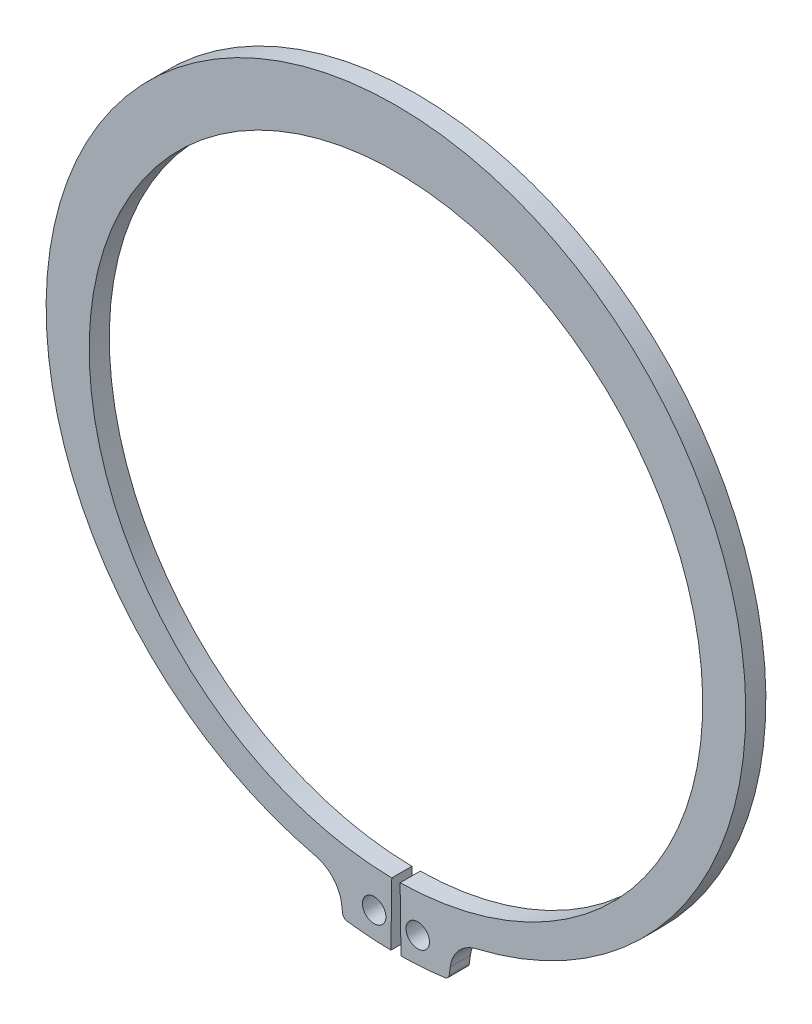
SolidWorks part; units mm, degrees
ref_plane "Plane1" through (0, 0, 0) normal (0, 0, 1) x (1, 0, 0)
ref_plane "Plane2" through (0, 0, 0) normal (0, 1, 0) x (1, 0, 0)
ref_plane "Plane3" through (0, 0, 0) normal (1, 0, 0) x (0, 0, -1)
sketch "Clipboard" plane through (0, 0, 0) normal (0, 0, 1) x (1, 0, 0)
  line L0 (0, 0) -> (8.6, 0)
  line L1 (0, 0) -> (0, 4.3)
  line L2 (0, 0) -> (0, -9.4)
  circle A0 centre (0, 0) radius 1.75
  circle A1 centre (0, 0) radius 47.5
  dimension "HoleDia" = 3.5
  dimension "ShaftDia" = 95
  dimension "LargeSection" = 8.6
  dimension "SmallSection" = 4.3
  dimension "LugSection" = 9.4
sketch "BodySke" plane through (0, 0, 0) normal (0, 0, 1) x (1, 0, 0)
  line L0 (-1.5431, 0) -> (1.5431, 0) construction
  line L1 (0, 0) -> (0, 54.35) construction
  line L2 (0.6222, -45.7458) -> (0.75, -55.1449)
  line L3 (-0.6222, -45.7458) -> (-0.75, -55.1449)
  line L4 (0, 0) -> (13.1537, -53.5584) construction
  line L5 (0, 0) -> (-13.1537, -53.5584) construction
  line L7 (8.0976, -52.8928) -> (7.9493, -54.0185)
  line L8 (-8.0976, -52.8928) -> (-7.9493, -54.0185)
  circle A0 centre (0, 0) radius 45.75 construction
  arc A1 (0.6222, -45.7458) -> (-0.6222, -45.7458) centre (0, 0) ccw
  arc A2 (11.9373, -48.6056) -> (-11.9373, -48.6056) centre (0, 2.1802) ccw construction
  arc A3 (0.75, -55.1449) -> (7.3051, -54.664) centre (0, 0) ccw
  arc A4 (11.9824, -48.595) -> (8.0976, -52.8928) centre (13.1537, -53.5584) ccw
  arc A5 (-8.0976, -52.8928) -> (-11.9824, -48.595) centre (-13.1537, -53.5584) ccw
  arc A6 (-7.3051, -54.664) -> (-0.75, -55.1449) centre (0, 0) ccw
  arc A7 (11.9824, -48.595) -> (-11.9824, -48.595) centre (0, 2.1802) ccw
  arc A8 (-8.395, -50.6338) -> (8.395, -50.6338) centre (0, 0) ccw construction
  circle A9 centre (3.25, -51.222) radius 1.75
  circle A10 centre (-3.25, -51.222) radius 1.75
  arc A11 (7.9493, -54.0185) -> (7.3051, -54.664) centre (7.2058, -53.9207) cw
  arc A12 (-7.9493, -54.0185) -> (-7.3051, -54.664) centre (-7.2058, -53.9207) ccw
  point P28 (7.8748, -54.5849)
  point P31 (-7.8748, -54.5849)
  dimension "HoleDia" = 3.5
  dimension "GrooveDia" = 91.5
  dimension "LugRad" = 55.15
  dimension "HoleOffsetRad" = 51.325
  dimension "D3" = 0.75
  dimension "LargeRad" = 54.35
  dimension "SmallRad" = 50.05
  dimension "SmallAngle" = 27.597
  dimension "D2" = 15
  dimension "HoleSpacing" = 6.5
  dimension "Gap" = 1.5
extrude "Body" add sketch "BodySke" against normal blind 3
sketch "NotSke" plane through (0, 0, 0) normal (0, 0, 1) x (1, 0, 0)
  line L0 (3.25, -49.472) -> (3.25, -52.972)
  line L1 (3.25, -52.972) -> (-3.25, -52.972)
  line L2 (-3.25, -52.972) -> (-3.25, -49.472)
  line L3 (-3.25, -49.472) -> (3.25, -49.472)
  circle A0 centre (3.25, -51.222) radius 1.75 construction
  circle A1 centre (-3.25, -51.222) radius 1.75 construction
extrude "Notch" [suppressed] cut sketch "NotSke" against normal through all
sketch "UnlSke" plane through (0, 0, 0) normal (0, 0, 1) x (1, 0, 0)
  line L0 (-5.3668, -54.8882) -> (-4.4521, -45.5329)
  line L1 (5.3668, -54.8882) -> (4.4521, -45.5329)
  arc A0 (4.4521, -45.5329) -> (-4.4521, -45.5329) centre (0, 0) ccw
  arc A1 (5.3668, -54.8882) -> (-5.3668, -54.8882) centre (0, 0) ccw
  arc A2 (0.75, -55.1449) -> (7.3051, -54.664) centre (0, 0) ccw construction
  arc A3 (0.6222, -45.7458) -> (-0.6222, -45.7458) centre (0, 0) ccw construction
  circle A4 centre (-3.25, -51.222) radius 1.75 construction
  circle A5 centre (3.25, -51.222) radius 1.75 construction
extrude "Unlug" [suppressed] add sketch "UnlSke" against normal through all
equation "' \"ShaftDia@Clipboard\" = 3"
equation "' \"Thickness@Body\" = 0.4"
equation "' \"GrooveDia@BodySke\" = 2.8"
equation "' \"LugSection@Clipboard\" = 1.9"
equation "' \"LargeSection@Clipboard\" = 0.8"
equation "' \"HoleDia@Clipboard\" = 1.0"
equation "' \"ShaftDia@Clipboard\" = 10"
equation "' \"Thickness@Body\" = 1.0"
equation "' \"GrooveDia@BodySke\" = 9.6"
equation "' \"LugSection@Clipboard\" = 3.3"
equation "' \"LargeSection@Clipboard\" = 1.8"
equation "' \"HoleDia@Clipboard\" = 1.5"
equation "\"SmallSection@Clipboard\" = \"LargeSection@Clipboard\" * 0.5"
equation "\"Gap@BodySke\" =  \"Thickness@Body\" / 2"
equation "\"LargeRad@BodySke\" =  \"GrooveDia@BodySke\" / 2 +  \"LargeSection@Clipboard\""
equation "\"SmallRad@BodySke\" =  \"GrooveDia@BodySke\" / 2 +  \"SmallSection@Clipboard\""
equation "\"LugRad@BodySke\" = \"GrooveDia@BodySke\" / 2 + \"LugSection@Clipboard\""
equation "\"HoleOffsetRad@BodySke\" = (  \"ShaftDia@Clipboard\" / 2 + \"LugRad@BodySke\" ) / 2"
equation "\"HoleSpacing@BodySke\" = \"Gap@BodySke\"  * 2 +  \"HoleDia@Clipboard\""
equation "\"HoleDia@BodySke\" =  \"HoleDia@Clipboard\""
equation "\"SmallAngle@BodySke\" = atn(\"HoleSpacing@BodySke\" / 2 / sqr(\"HoleOffsetRad@BodySke\"  * \"HoleOffsetRad@BodySke\" - (\"HoleSpacing@BodySke\" / 2) * (\"HoleSpacing@BodySke\" / 2) ))  * 7 *  (\"LargeRad@BodySke\" / \"SmallRad@BodySke\")* ( 180 / 3.141593)"
